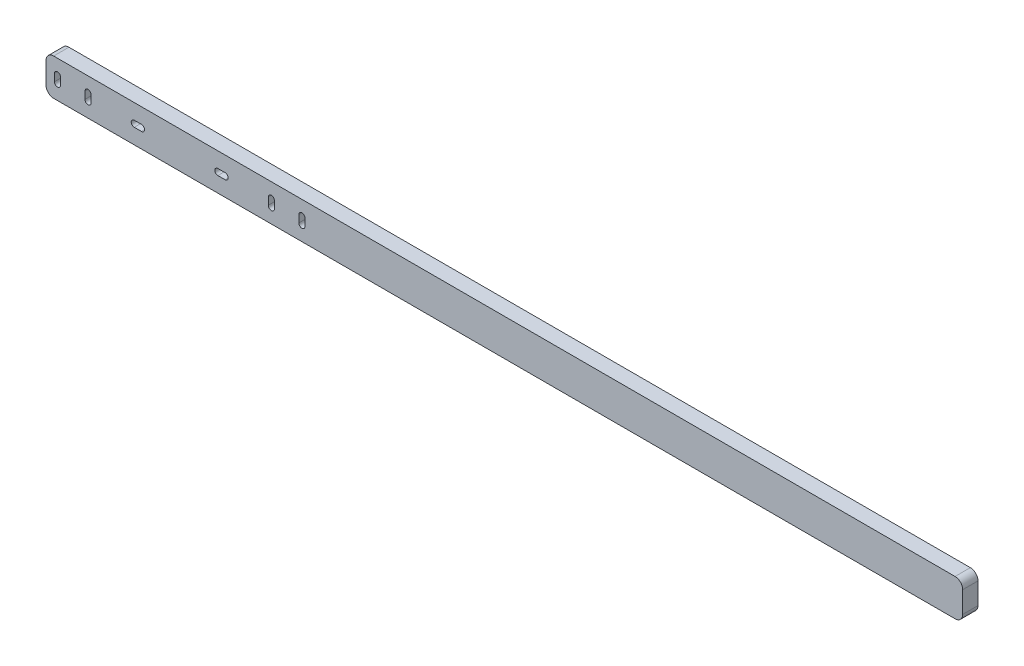
SolidWorks part; units mm, degrees
ref_plane "Alzado" through (0, 0, 0) normal (0, 0, 1) x (1, 0, 0)
ref_plane "Planta" through (0, 0, 0) normal (0, 1, 0) x (1, 0, 0)
ref_plane "Vista lateral" through (0, 0, 0) normal (1, 0, 0) x (0, 0, -1)
sketch "Croquis1" plane through (0, 0, 0) normal (0, 0, 1) x (1, 0, 0)
  line L0 (-190.5, 0) -> (0, 0) construction
  line L1 (-187.325, -7.62) -> (187.325, -7.62)
  line L2 (-190.5, -4.445) -> (-190.5, 4.445)
  line L3 (-187.325, 7.62) -> (187.325, 7.62)
  line L4 (190.5, -4.445) -> (190.5, 4.445)
  line L5 (-190.5, -7.62) -> (190.5, 7.62) construction
  line L6 (-190.5, 7.62) -> (190.5, -7.62) construction
  line L7 (-185.7375, -1.5) -> (-185.7375, 1.5) construction
  line L8 (-187.0075, -1.5) -> (-187.0075, 1.5)
  line L9 (-184.4675, -1.5) -> (-184.4675, 1.5)
  line L10 (-96.8375, -1.5) -> (-96.8375, 1.5) construction
  line L11 (-98.1075, -1.5) -> (-98.1075, 1.5)
  line L12 (-95.5675, -1.5) -> (-95.5675, 1.5)
  line L13 (-179.3875, 0) -> (-179.3875, 7.62) construction
  line L14 (-173.0375, -1.5) -> (-173.0375, 1.5) construction
  line L15 (-171.7675, -1.5) -> (-171.7675, 1.5)
  line L16 (-174.3075, -1.5) -> (-174.3075, 1.5)
  line L17 (-90.4875, 0) -> (-90.4875, 7.62) construction
  line L18 (-84.1375, -1.5) -> (-84.1375, 1.5) construction
  line L19 (-82.8675, -1.5) -> (-82.8675, 1.5)
  line L20 (-85.4075, -1.5) -> (-85.4075, 1.5)
  line L21 (-153.8125, 0) -> (-150.8125, 0) construction
  line L22 (-153.8125, 1.27) -> (-150.8125, 1.27)
  line L23 (-153.8125, -1.27) -> (-150.8125, -1.27)
  line L24 (-134.9375, 7.62) -> (-134.9375, -7.62) construction
  line L25 (-116.0625, 0) -> (-119.0625, 0) construction
  line L26 (-116.0625, 1.27) -> (-119.0625, 1.27)
  line L27 (-116.0625, -1.27) -> (-119.0625, -1.27)
  arc A0 (-187.0075, -1.5) -> (-184.4675, -1.5) centre (-185.7375, -1.5) ccw
  arc A1 (-184.4675, 1.5) -> (-187.0075, 1.5) centre (-185.7375, 1.5) ccw
  arc A2 (187.325, -7.62) -> (190.5, -4.445) centre (187.325, -4.445) ccw
  arc A3 (187.325, 7.62) -> (190.5, 4.445) centre (187.325, 4.445) cw
  arc A4 (-187.325, -7.62) -> (-190.5, -4.445) centre (-187.325, -4.445) cw
  arc A5 (-190.5, 4.445) -> (-187.325, 7.62) centre (-187.325, 4.445) cw
  arc A6 (-98.1075, -1.5) -> (-95.5675, -1.5) centre (-96.8375, -1.5) ccw
  arc A7 (-95.5675, 1.5) -> (-98.1075, 1.5) centre (-96.8375, 1.5) ccw
  arc A8 (-171.7675, -1.5) -> (-174.3075, -1.5) centre (-173.0375, -1.5) cw
  arc A9 (-174.3075, 1.5) -> (-171.7675, 1.5) centre (-173.0375, 1.5) cw
  arc A10 (-82.8675, -1.5) -> (-85.4075, -1.5) centre (-84.1375, -1.5) cw
  arc A11 (-85.4075, 1.5) -> (-82.8675, 1.5) centre (-84.1375, 1.5) cw
  arc A12 (-153.8125, 1.27) -> (-153.8125, -1.27) centre (-153.8125, 0) ccw
  arc A13 (-150.8125, -1.27) -> (-150.8125, 1.27) centre (-150.8125, 0) ccw
  arc A14 (-116.0625, 1.27) -> (-116.0625, -1.27) centre (-116.0625, 0) cw
  arc A15 (-119.0625, -1.27) -> (-119.0625, 1.27) centre (-119.0625, 0) cw
  point P0 (0, 0)
  point P9 (-185.7375, 0)
  point P29 (-96.8375, 0)
  point P38 (-173.0375, 0)
  point P47 (-84.1375, 0)
  point P54 (-152.3125, 0)
  point P63 (-117.5625, 0)
  dimension "D3" = 1.27
  dimension "D6" = 3.175
  dimension "D1" = 381
  dimension "D2" = 15.24
  dimension "D4" = 4.7625
  dimension "D5" = 3
  dimension "D7" = 88.9
  dimension "D8" = 10.16
  dimension "D9" = 10.16
  dimension "D10" = 31.75
extrude "Saliente-Extruir1" add sketch "Croquis1" along normal blind 6.35
